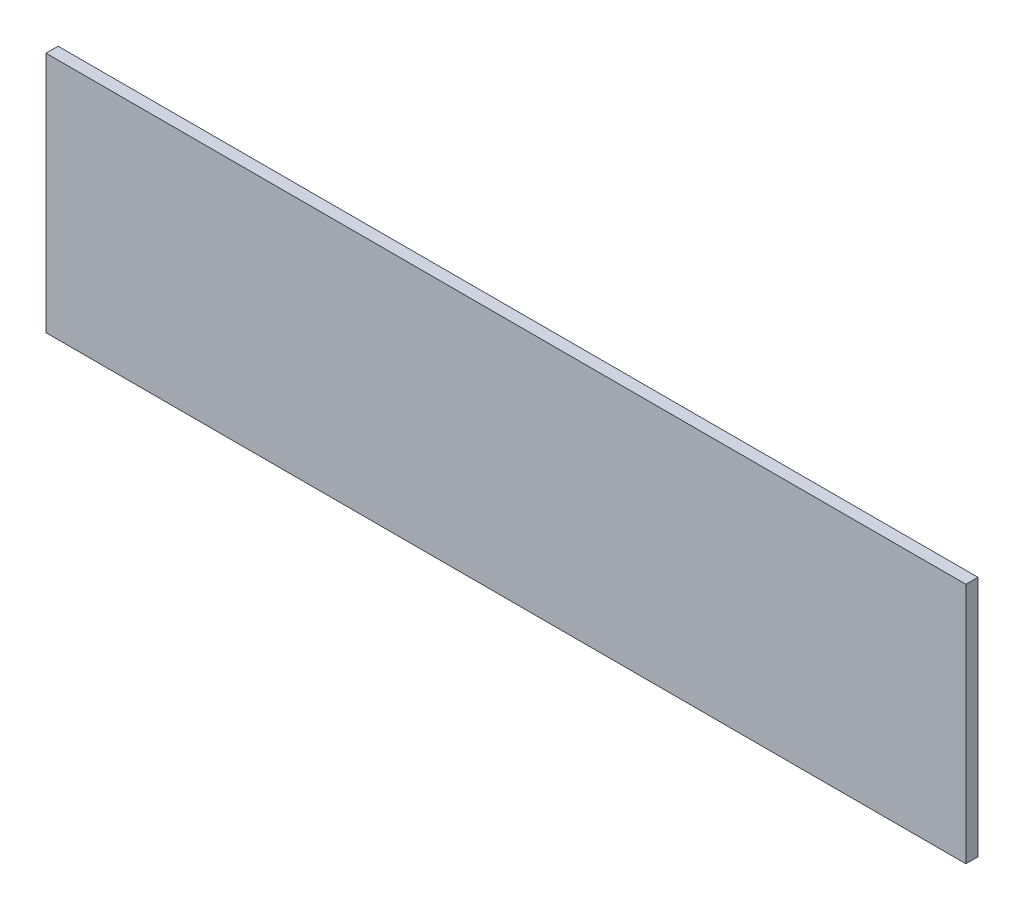
SolidWorks part; units mm, degrees
ref_plane "Plan de face" through (0, 0, 0) normal (0, 0, 1) x (1, 0, 0)
ref_plane "Plan de dessus" through (0, 0, 0) normal (0, 1, 0) x (1, 0, 0)
ref_plane "Plan de droite" through (0, 0, 0) normal (1, 0, 0) x (0, 0, -1)
sketch "Esquisse1" plane through (0, 0, 0) normal (0, 0, 1) x (1, 0, 0)
  line L1 (-139.4457, 100.7193) -> (240.5543, 100.7193)
  line L2 (-139.4457, 100.7193) -> (-139.4457, 0.7193)
  line L3 (-139.4457, 0.7193) -> (240.5543, 0.7193)
  line L4 (240.5543, 100.7193) -> (240.5543, 0.7193)
  dimension "D1" = 380
  dimension "D2" = 100
extrude "Boss.-Extru.1" add sketch "Esquisse1" along normal blind 5
